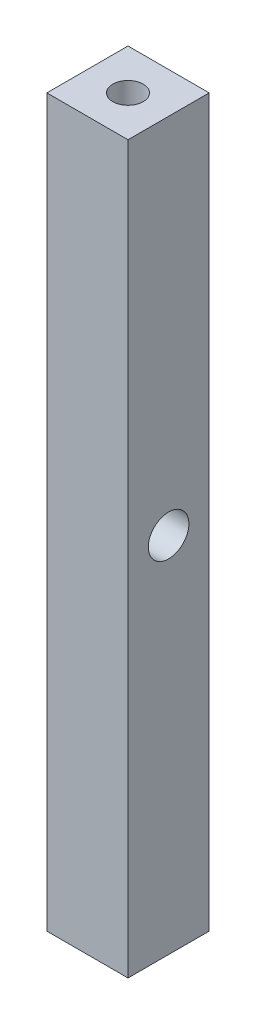
SolidWorks part; units mm, degrees
ref_plane "Front Plane" through (0, 0, 0) normal (0, 0, 1) x (1, 0, 0)
ref_plane "Top Plane" through (0, 0, 0) normal (0, 1, 0) x (1, 0, 0)
ref_plane "Right Plane" through (0, 0, 0) normal (1, 0, 0) x (0, 0, -1)
sketch "Sketch1" plane through (0, 0, 0) normal (0, 1, 0) x (1, 0, 0)
  line L1 (-4, -4) -> (4, -4)
  line L2 (-4, -4) -> (-4, 4)
  line L3 (-4, 4) -> (4, 4)
  line L4 (4, -4) -> (4, 4)
  line L5 (-4, -4) -> (4, 4) construction
  line L6 (-4, 4) -> (4, -4) construction
  circle A0 centre (0, 0) radius 1.5
  point P0 (0, 0)
  dimension "D3" = 3
  dimension "D1" = 8
  dimension "D2" = 8
extrude "Boss-Extrude1" add sketch "Sketch1" along normal blind 71.54
sketch "Sketch2" plane through (4, 0, 0) normal (1, 0, 0) x (0, 0, -1)
  line L1 (-4, 71.54) -> (4, 71.54) construction
  circle A0 centre (0, 35.77) radius 2
  point P5 (0, 0)
  dimension "D1" = 4
  dimension "D2" = 35.77
extrude "Cut-Extrude1" cut sketch "Sketch2" against normal up to next
